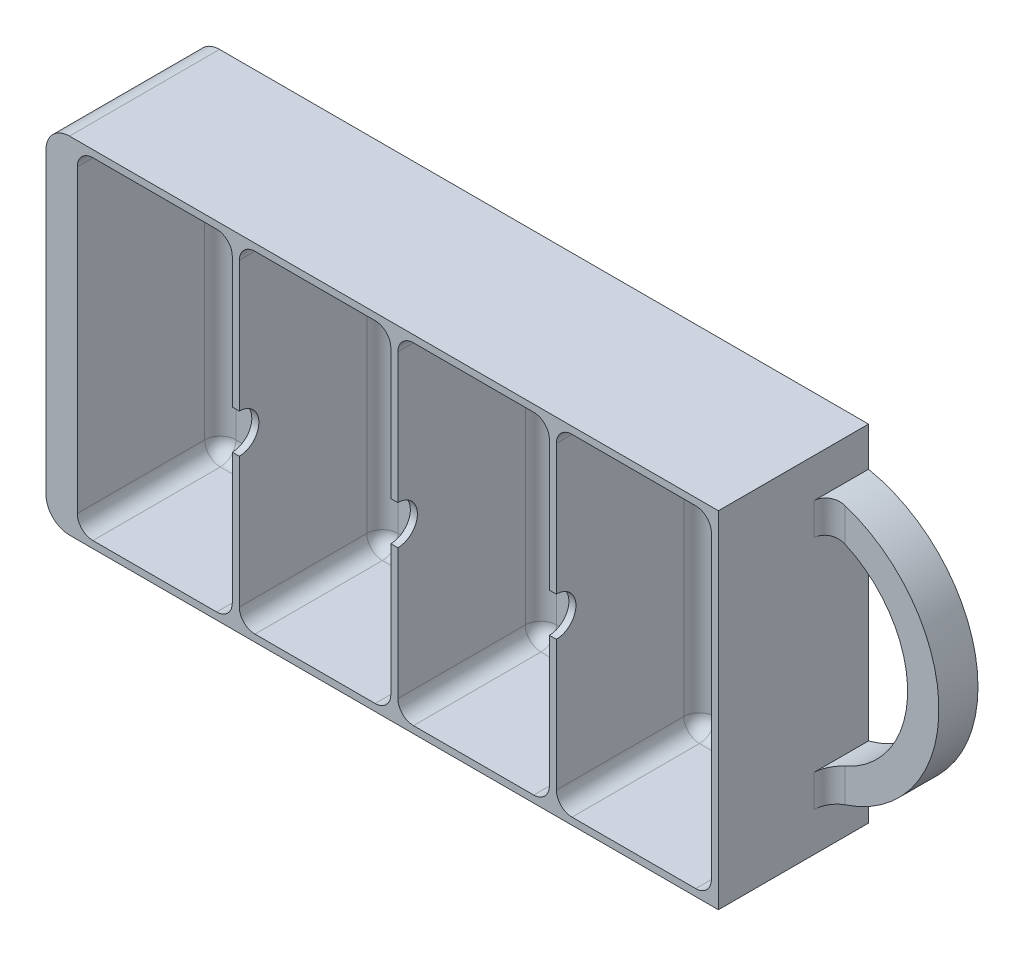
SolidWorks part; units mm, degrees
ref_plane "Спереди" through (0, 0, 0) normal (0, 0, 1) x (1, 0, 0)
ref_plane "Сверху" through (0, 0, 0) normal (0, 1, 0) x (1, 0, 0)
ref_plane "Справа" through (0, 0, 0) normal (1, 0, 0) x (0, 0, -1)
ref_plane "Плоскость4" through (0, 0, 9.6) normal (0, 0, 1) x (1, 0, 0)
sketch "Эскиз1" plane through (0, 0, 9.6) normal (0, 0, 1) x (1, 0, 0)
  line L0 (90, -22.1) -> (90, 22.1)
  line L1 (90, 22.1) -> (4, 22.1)
  line L2 (4, 22.1) -> (4, -22.1)
  line L3 (4, -22.1) -> (90, -22.1)
extrude "Бобышка-Вытянуть1" add sketch "Эскиз1" against normal blind 14.2
sketch "Эскиз2" plane through (0, 0, -4.6) normal (0, 0, -1) x (-1, 0, 0)
  line L0 (-90, -22.1) -> (-90, -17.1)
  line L1 (-90, 17.1) -> (-90, 22.1)
  line L2 (-90, 22.1) -> (-4, 22.1)
  line L3 (-4, 22.1) -> (-4, -22.1)
  line L4 (-4, -22.1) -> (-90, -22.1)
  line L5 (-90, -12.9948) -> (-90, 12.9948)
  arc A0 (-90, -17.1) -> (-90, 17.1) centre (-86.5568, 0) cw
  arc A1 (-90, 12.9948) -> (-90, -12.9948) centre (-86.5568, 0) ccw
extrude "Бобышка-Вытянуть2" add sketch "Эскиз2" along normal blind 5
sketch "Эскиз3" plane through (0, 0, 9.6) normal (0, 0, 1) x (1, 0, 0)
  line L0 (69.275, 21.2) -> (69.275, -21.2)
  line L1 (69.275, -21.2) -> (89.1, -21.2)
  line L2 (89.1, -21.2) -> (89.1, 21.2)
  line L3 (89.1, 21.2) -> (69.275, 21.2)
extrude "Вырез-Вытянуть1" cut sketch "Эскиз3" against normal blind 18.3
sketch "Эскиз4" plane through (0, 0, 9.6) normal (0, 0, 1) x (1, 0, 0)
  line L0 (49, -21.2) -> (68.375, -21.2)
  line L1 (68.375, -21.2) -> (68.375, 21.2)
  line L2 (68.375, 21.2) -> (49, 21.2)
  line L3 (49, 21.2) -> (49, -21.2)
extrude "Вырез-Вытянуть2" cut sketch "Эскиз4" against normal blind 18.3
sketch "Эскиз5" plane through (0, 0, 9.6) normal (0, 0, 1) x (1, 0, 0)
  line L0 (28.725, -21.2) -> (48.1, -21.2)
  line L1 (48.1, -21.2) -> (48.1, 21.2)
  line L2 (48.1, 21.2) -> (28.725, 21.2)
  line L3 (28.725, 21.2) -> (28.725, -21.2)
extrude "Вырез-Вытянуть3" cut sketch "Эскиз5" against normal blind 18.3
sketch "Эскиз6" plane through (0, 0, 9.6) normal (0, 0, 1) x (1, 0, 0)
  line L0 (27.825, -21.2) -> (27.825, 21.2)
  line L1 (27.825, 21.2) -> (8, 21.2)
  line L2 (8, 21.2) -> (8, -21.2)
  line L3 (8, -21.2) -> (27.825, -21.2)
extrude "Вырез-Вытянуть4" cut sketch "Эскиз6" against normal blind 18.3
hole_wizard "Диаметр отверстия Ø8.3 (8.3)1" positions "Эскиз8" profile "Эскиз7" hole size "Ø8.3" standard "Ansi Metric"
sketch "Эскиз8" plane through (4, 0, 0) normal (-1, 0, 0) x (0, 0, 1)
  point P0 (0, 0)
sketch "Эскиз7" plane through (4, 0, 0) normal (0, 1, 0) x (0, 0, 1)
  line L0 (0, 0) -> (0, 3.2)
  line L1 (0, 3.2) -> (4.15, 3.2)
  line L2 (4.15, 3.2) -> (4.15, 0)
  line L5 (4.15, 0) -> (0, 0)
  line L10 (0, 3.2) -> (-4.15, 3.2) construction
  line L11 (0, -6.35) -> (0, 107.95) construction
  dimension "Диаметр отверстия" = 8.3
  dimension "Глубина отверстия" = 3.2
  dimension "Угол заточки сверла" = 180
hole_wizard "Диаметр отверстия Ø5.0 (5)1" positions "Эскиз10" profile "Эскиз9" hole size "Ø5.0" standard "Ansi Metric"
sketch "Эскиз10" plane through (28.725, 0, 0) normal (1, 0, 0) x (0, 0, -1)
  point P0 (-9.6, 0)
sketch "Эскиз9" plane through (28.725, 0, 9.6) normal (0, 1, 0) x (0, 0, -1)
  line L0 (0, 0) -> (0, 0.9)
  line L1 (0, 0.9) -> (2.5, 0.9)
  line L2 (2.5, 0.9) -> (2.5, 0)
  line L5 (2.5, 0) -> (0, 0)
  line L11 (0, -6.35) -> (0, 107.95) construction
  dimension "Диаметр сквозного отверстия" = 5
  dimension "Глубина сквозного отверстия" = 0.9
hole_wizard "Диаметр отверстия Ø5.0 (5)2" positions "Эскиз12" profile "Эскиз11" hole size "Ø5.0" standard "Ansi Metric"
sketch "Эскиз12" plane through (48.1, 0, 0) normal (-1, 0, 0) x (0, 0, 1)
  point P0 (9.6, 0)
sketch "Эскиз11" plane through (48.1, 0, 9.6) normal (0, 1, 0) x (0, 0, 1)
  line L0 (0, 0) -> (0, 0.9)
  line L1 (0, 0.9) -> (2.5, 0.9)
  line L2 (2.5, 0.9) -> (2.5, 0)
  line L5 (2.5, 0) -> (0, 0)
  line L11 (0, -6.35) -> (0, 107.95) construction
  dimension "Диаметр сквозного отверстия" = 5
  dimension "Глубина сквозного отверстия" = 0.9
hole_wizard "Диаметр отверстия Ø5.0 (5)3" positions "Эскиз14" profile "Эскиз13" hole size "Ø5.0" standard "Ansi Metric"
sketch "Эскиз14" plane through (68.375, 0, 0) normal (-1, 0, 0) x (0, 0, 1)
  point P0 (9.6, 0)
sketch "Эскиз13" plane through (68.375, 0, 9.6) normal (0, 1, 0) x (0, 0, 1)
  line L0 (0, 0) -> (0, 0.9)
  line L1 (0, 0.9) -> (2.5, 0.9)
  line L2 (2.5, 0.9) -> (2.5, 0)
  line L5 (2.5, 0) -> (0, 0)
  line L11 (0, -6.35) -> (0, 107.95) construction
  dimension "Диаметр сквозного отверстия" = 5
  dimension "Глубина сквозного отверстия" = 0.9
fillet "Скругление1" radius 3 2 edges at (4, -22.1, 0) (4, 22.1, 0)
sketch "Эскиз15" plane through (4, 0, 0) normal (-1, 0, 0) x (0, 0, 1)
  circle A0 centre (0, 0) radius 4.15 construction
  circle A1 centre (0, 0) radius 4.15
extrude "Бобышка-Вытянуть3" add sketch "Эскиз15" against normal blind 3.5
fillet "Скругление3" radius 2 34 edges at (89.1, 0, -8.7) (79.1875, -21.2, -8.7) (69.275, 0, -8.7) (79.1875, 21.2, -8.7) (58.6875, 21.2, -8.7) (68.375, 0, -8.7) (58.6875, -21.2, -8.7) (49, 0, -8.7) (38.4125, 21.2, -8.7) (48.1, 0, -8.7) (38.4125, -21.2, -8.7) (28.725, 0, -8.7) (8, 0, -8.7) (17.9125, 21.2, -8.7) (27.825, 0, -8.7) (17.9125, -21.2, -8.7) (90, -15.0474, -4.6) (90, 15.0474, -4.6) (28.725, -21.2, 0.45) (49, -21.2, 0.45) (69.275, -21.2, 0.45) (89.1, -21.2, 0.45) (68.375, -21.2, 0.45) (48.1, -21.2, 0.45) (27.825, -21.2, 0.45) (8, -21.2, 0.45) (89.1, 21.2, 0.45) (69.275, 21.2, 0.45) (68.375, 21.2, 0.45) (49, 21.2, 0.45) (48.1, 21.2, 0.45) (28.725, 21.2, 0.45) (27.825, 21.2, 0.45) (8, 21.2, 0.45)
